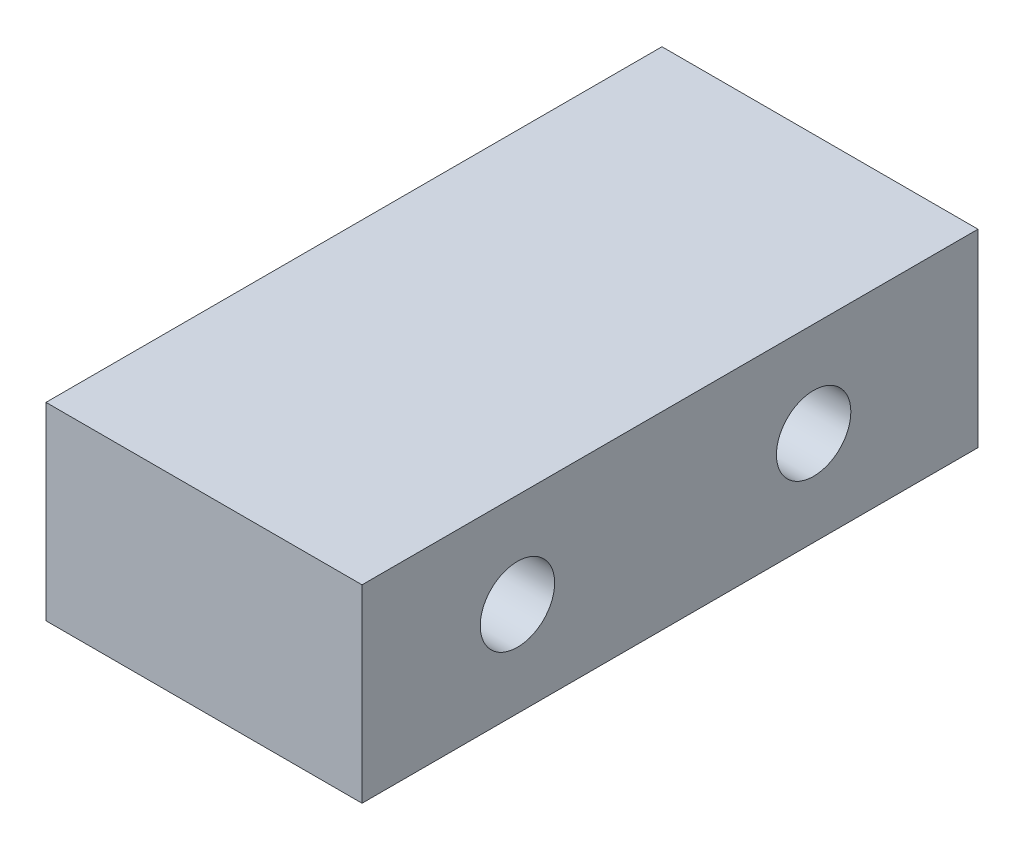
SolidWorks part; units mm, degrees
ref_plane "Front Plane" through (0, 0, 0) normal (0, 0, 1) x (1, 0, 0)
ref_plane "Top Plane" through (0, 0, 0) normal (0, 1, 0) x (1, 0, 0)
ref_plane "Right Plane" through (0, 0, 0) normal (1, 0, 0) x (0, 0, -1)
sketch "Sketch1" plane through (0, 0, 0) normal (0, 1, 0) x (1, 0, 0)
  line L1 (-5.095, -9.93) -> (5.095, -9.93)
  line L2 (-5.095, -9.93) -> (-5.095, 9.93)
  line L3 (-5.095, 9.93) -> (5.095, 9.93)
  line L4 (5.095, -9.93) -> (5.095, 9.93)
  line L5 (-5.095, -9.93) -> (5.095, 9.93) construction
  line L6 (-5.095, 9.93) -> (5.095, -9.93) construction
  point P0 (0, 0)
  dimension "D1" = 10.19
  dimension "D2" = 19.86
extrude "Boss-Extrude1" add sketch "Sketch1" along normal blind 6.1
sketch "Sketch2" plane through (5.095, 0, 0) normal (1, 0, 0) x (0, 0, -1)
  line L1 (-9.93, 6.1) -> (9.93, 6.1) construction
  line L2 (9.93, 6.1) -> (9.93, 0) construction
  circle A0 centre (4.63, 3.05) radius 1.2
  circle A1 centre (-4.92, 3.05) radius 1.2
  dimension "D1" = 2.4
  dimension "D2" = 2.4
  dimension "D3" = 9.55
  dimension "D4" = 3.05
  dimension "D5" = 3.05
  dimension "D6" = 5.3
extrude "Cut-Extrude1" cut sketch "Sketch2" against normal through all
